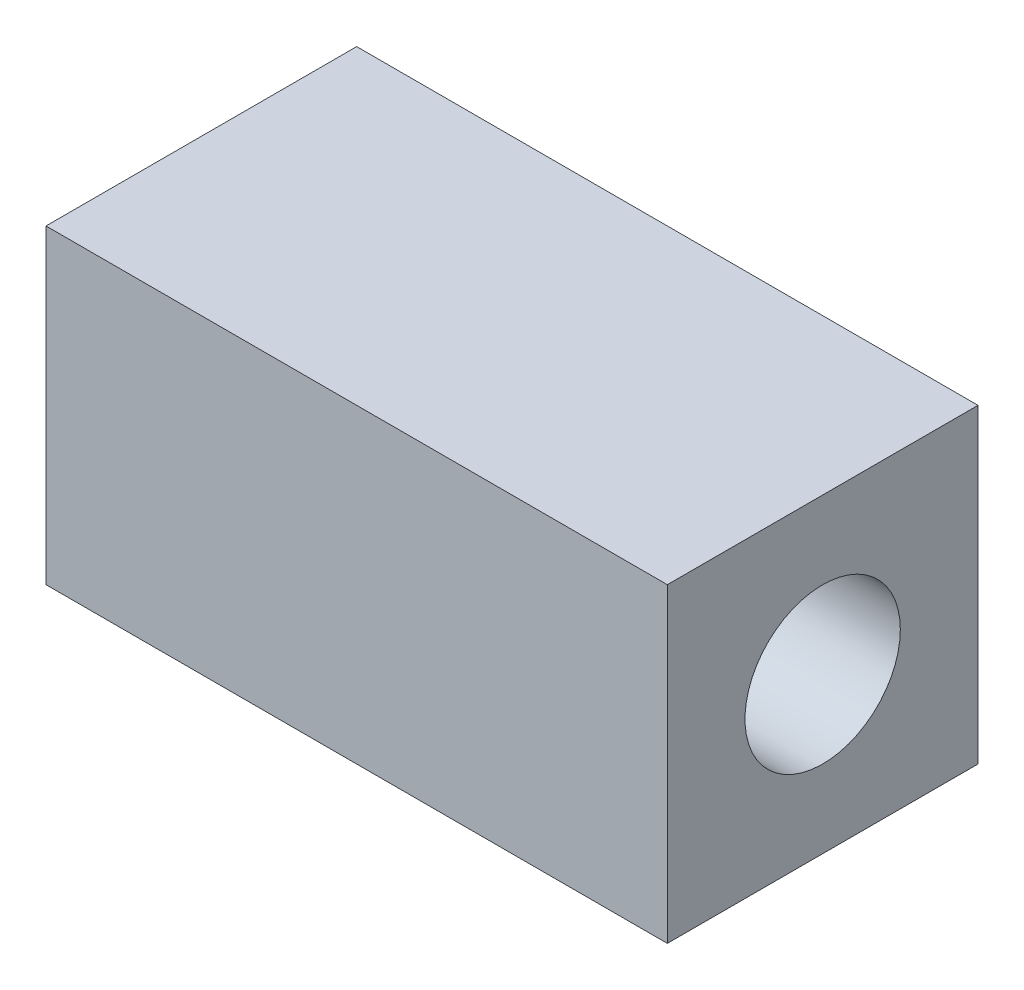
SolidWorks part; units mm, degrees
ref_plane "Alzado" through (0, 0, 0) normal (0, 0, 1) x (1, 0, 0)
ref_plane "Planta" through (0, 0, 0) normal (0, 1, 0) x (1, 0, 0)
ref_plane "Vista lateral" through (0, 0, 0) normal (1, 0, 0) x (0, 0, -1)
sketch "Croquis1" plane through (0, 0, 0) normal (1, 0, 0) x (0, 0, -1)
  line L1 (0, 0) -> (20, 0)
  line L2 (0, 0) -> (0, 20)
  line L3 (0, 20) -> (20, 20)
  line L4 (20, 0) -> (20, 20)
  circle A0 centre (10, 10) radius 5
  dimension "D3" = 10
  dimension "D1" = 20
  dimension "D2" = 20
extrude "Saliente-Extruir1" add sketch "Croquis1" along normal blind 40
